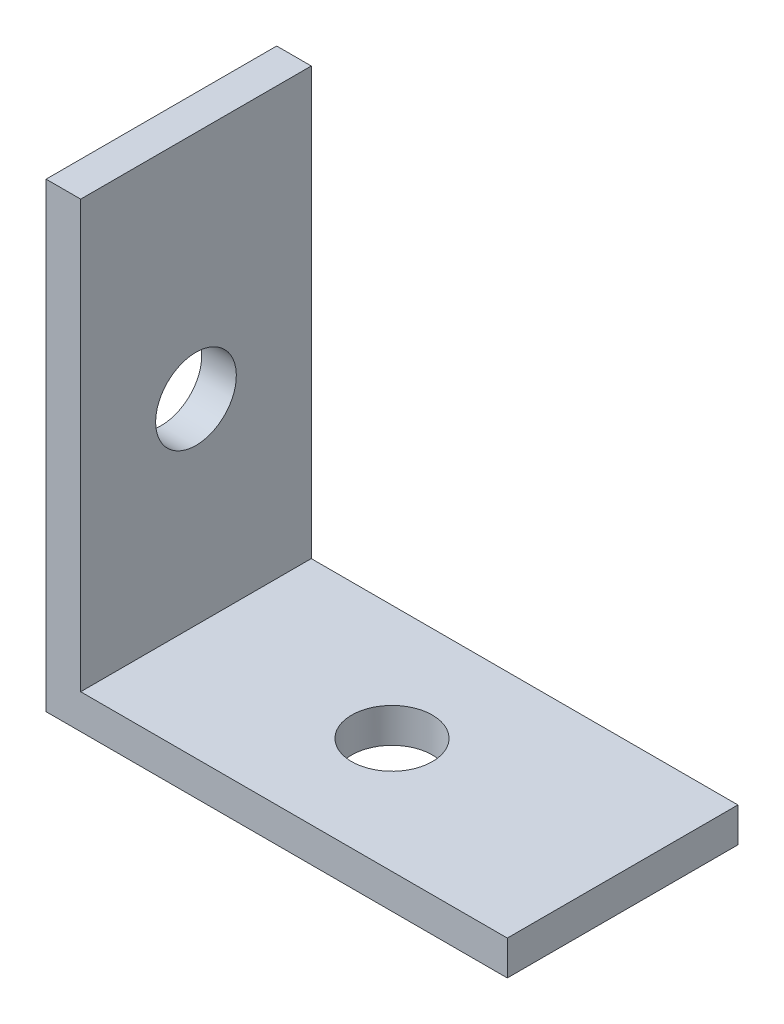
SolidWorks part; units mm, degrees
ref_plane "Спереди" through (0, 0, 0) normal (0, 0, 1) x (1, 0, 0)
ref_plane "Сверху" through (0, 0, 0) normal (0, 1, 0) x (1, 0, 0)
ref_plane "Справа" through (0, 0, 0) normal (1, 0, 0) x (0, 0, -1)
sketch "Эскиз2" plane through (0, 0, 0) normal (0, 0, 1) x (1, 0, 0)
  line L0 (0, 0) -> (0, 20)
  line L1 (0, 20) -> (1.5, 20)
  line L2 (1.5, 20) -> (1.5, 1.5)
  line L3 (1.5, 1.5) -> (20, 1.5)
  line L4 (20, 1.5) -> (20, 0)
  line L5 (20, 0) -> (0, 0)
  point P5 (0, 0)
  dimension "D1" = 20
  dimension "D2" = 1.5
extrude "Бобышка-Вытянуть1" add sketch "Эскиз2" along normal blind 10
sketch "Эскиз3" plane through (0, 0, 0) normal (0, -1, 0) x (1, 0, 0)
  line L0 (0, 10) -> (0, 0) construction
  line L1 (0, 10) -> (20, 10) construction
  circle A0 centre (10, 5) radius 1.75
  point P2 (0, 0)
  point P5 (0, 5)
  point P6 (0, 0)
  point P9 (10, 10)
  dimension "D1" = 3.5
extrude "Вырез-Вытянуть1" cut sketch "Эскиз3" against normal up to next
ref_plane "Плоскость1" through (0, 0, 0) normal (-0.7071, 0.7071, 0) x (0.7071, 0.7071, 0)
mirror "Зеркальное отражение1" about plane through (0, 0, 0) normal (-0.7071, 0.7071, 0) of "Вырез-Вытянуть1"
equation "\"ATX.Case.01.Profile.20.Width\"=20"
equation "\"ATX.Case.01.Profile.20.Thickness\" = 1.5"
equation "\"ATX.Case.01.Profile.10.Width\"=10"
equation "\"D1@Эскиз2\"= \"ATX.Case.01.Profile.20.Width\""
equation "\"D2@Эскиз2\"= \"ATX.Case.01.Profile.20.Thickness\""
equation "\"D1@Бобышка-Вытянуть1\"= \"ATX.Case.01.Profile.10.Width\""
